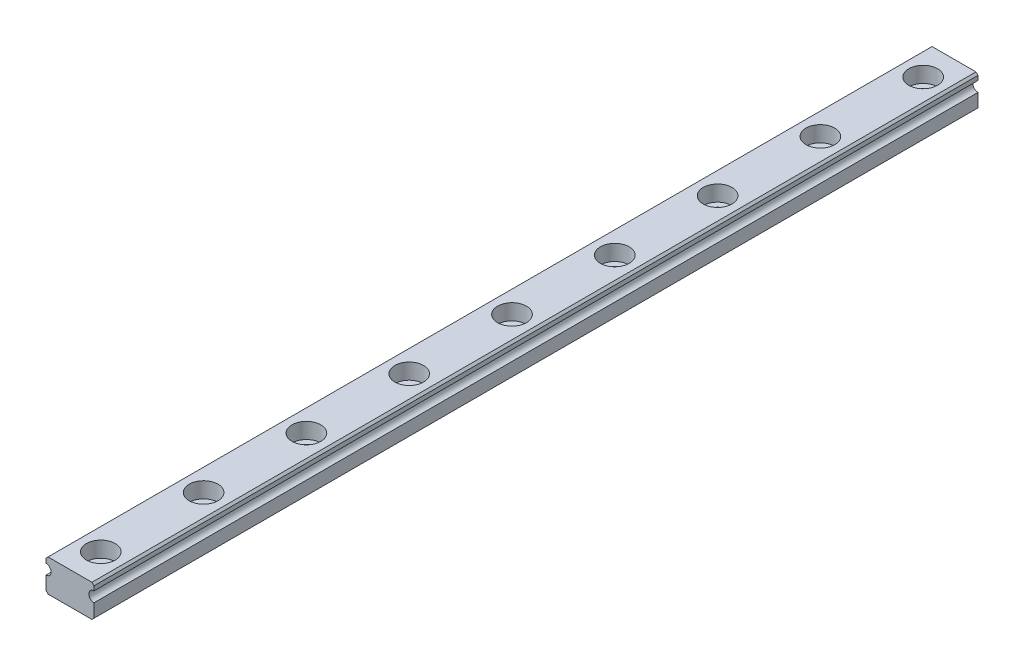
SolidWorks part; units mm, degrees
material "Plain Carbon Steel"
ref_plane "Front Plane" through (0, 0, 0) normal (0, 0, 1) x (1, 0, 0)
ref_plane "Top Plane" through (0, 0, 0) normal (0, 1, 0) x (1, 0, 0)
ref_plane "Right Plane" through (0, 0, 0) normal (1, 0, 0) x (0, 0, -1)
ref_plane "Plane1" through (0, 0, 0) normal (0, 0, 1) x (1, 0, 0)
sketch "Sketch1" plane through (0, 0, 0) normal (0, 0, 1) x (1, 0, 0)
  line L0 (-3.5, 4.403) -> (-3.5, 3.76)
  line L1 (-3.5, 2.26) -> (-3.5, 0.3)
  line L2 (-3.5, 0.3) -> (-3.2, 0)
  line L3 (-3.2, 0) -> (3.2, 0)
  line L4 (3.2, 0) -> (3.5, 0.3)
  line L5 (3.5, 0.3) -> (3.5, 2.26)
  line L6 (3.5, 3.76) -> (3.5, 4.403)
  line L7 (3.5, 4.403) -> (3.203, 4.7)
  line L8 (3.203, 4.7) -> (-3.203, 4.7)
  line L9 (-3.203, 4.7) -> (-3.5, 4.403)
  arc A0 (-3.5, 3.76) -> (-3.5, 2.26) centre (-3.5, 3.01) cw
  arc A1 (3.5, 2.26) -> (3.5, 3.76) centre (3.5, 3.01) cw
extrude "Boss-Extrude1" add sketch "Sketch1" along normal blind 129
ref_plane "Plane2" through (0, 0, 0) normal (1, 0, 0) x (0, 0, -1)
sketch "Sketch2" plane through (0, 0, 0) normal (1, 0, 0) x (0, 0, -1)
  line L0 (-4.5, 4.7) -> (-2.4, 4.7)
  line L1 (-2.4, 4.7) -> (-2.4, 2.4)
  line L2 (-2.4, 2.4) -> (-3.3, 2.4)
  line L3 (-3.3, 2.4) -> (-3.3, 0)
  line L4 (-3.3, 0) -> (-4.5, 0)
  line L5 (-4.5, 0) -> (-4.5, 4.7)
  line L6 (-4.5, 0) -> (-4.5, 4.7) construction
revolve "Cut-Revolve1" cut sketch "Sketch2" angle 360 about L6
ref_plane "Plane3" through (0, 0, 0) normal (1, 0, 0) x (0, 0, -1)
sketch "Sketch3" plane through (0, 0, 0) normal (1, 0, 0) x (0, 0, -1)
  line L0 (-124.5, 4.7) -> (-122.4, 4.7)
  line L1 (-122.4, 4.7) -> (-122.4, 2.4)
  line L2 (-122.4, 2.4) -> (-123.3, 2.4)
  line L3 (-123.3, 2.4) -> (-123.3, 0)
  line L4 (-123.3, 0) -> (-124.5, 0)
  line L5 (-124.5, 0) -> (-124.5, 4.7)
  line L6 (-124.5, 0) -> (-124.5, 4.7) construction
revolve "Cut-Revolve2" cut sketch "Sketch3" angle 360 about L6
ref_plane "Plane4" through (0, 0, 0) normal (1, 0, 0) x (0, 0, -1)
sketch "Sketch4" plane through (0, 0, 0) normal (1, 0, 0) x (0, 0, -1)
  line L0 (-109.5, 4.7) -> (-107.4, 4.7)
  line L1 (-107.4, 4.7) -> (-107.4, 2.4)
  line L2 (-107.4, 2.4) -> (-108.3, 2.4)
  line L3 (-108.3, 2.4) -> (-108.3, 0)
  line L4 (-108.3, 0) -> (-109.5, 0)
  line L5 (-109.5, 0) -> (-109.5, 4.7)
  line L6 (-109.5, 0) -> (-109.5, 4.7) construction
revolve "Cut-Revolve3" cut sketch "Sketch4" angle 360 about L6
ref_plane "Plane5" through (0, 0, 0) normal (1, 0, 0) x (0, 0, -1)
sketch "Sketch5" plane through (0, 0, 0) normal (1, 0, 0) x (0, 0, -1)
  line L0 (-94.5, 4.7) -> (-92.4, 4.7)
  line L1 (-92.4, 4.7) -> (-92.4, 2.4)
  line L2 (-92.4, 2.4) -> (-93.3, 2.4)
  line L3 (-93.3, 2.4) -> (-93.3, 0)
  line L4 (-93.3, 0) -> (-94.5, 0)
  line L5 (-94.5, 0) -> (-94.5, 4.7)
  line L6 (-94.5, 0) -> (-94.5, 4.7) construction
revolve "Cut-Revolve4" cut sketch "Sketch5" angle 360 about L6
ref_plane "Plane6" through (0, 0, 0) normal (1, 0, 0) x (0, 0, -1)
sketch "Sketch6" plane through (0, 0, 0) normal (1, 0, 0) x (0, 0, -1)
  line L0 (-79.5, 4.7) -> (-77.4, 4.7)
  line L1 (-77.4, 4.7) -> (-77.4, 2.4)
  line L2 (-77.4, 2.4) -> (-78.3, 2.4)
  line L3 (-78.3, 2.4) -> (-78.3, 0)
  line L4 (-78.3, 0) -> (-79.5, 0)
  line L5 (-79.5, 0) -> (-79.5, 4.7)
  line L6 (-79.5, 0) -> (-79.5, 4.7) construction
revolve "Cut-Revolve5" cut sketch "Sketch6" angle 360 about L6
ref_plane "Plane7" through (0, 0, 0) normal (1, 0, 0) x (0, 0, -1)
sketch "Sketch7" plane through (0, 0, 0) normal (1, 0, 0) x (0, 0, -1)
  line L0 (-64.5, 4.7) -> (-62.4, 4.7)
  line L1 (-62.4, 4.7) -> (-62.4, 2.4)
  line L2 (-62.4, 2.4) -> (-63.3, 2.4)
  line L3 (-63.3, 2.4) -> (-63.3, 0)
  line L4 (-63.3, 0) -> (-64.5, 0)
  line L5 (-64.5, 0) -> (-64.5, 4.7)
  line L6 (-64.5, 0) -> (-64.5, 4.7) construction
revolve "Cut-Revolve6" cut sketch "Sketch7" angle 360 about L6
ref_plane "Plane8" through (0, 0, 0) normal (1, 0, 0) x (0, 0, -1)
sketch "Sketch8" plane through (0, 0, 0) normal (1, 0, 0) x (0, 0, -1)
  line L0 (-49.5, 4.7) -> (-47.4, 4.7)
  line L1 (-47.4, 4.7) -> (-47.4, 2.4)
  line L2 (-47.4, 2.4) -> (-48.3, 2.4)
  line L3 (-48.3, 2.4) -> (-48.3, 0)
  line L4 (-48.3, 0) -> (-49.5, 0)
  line L5 (-49.5, 0) -> (-49.5, 4.7)
  line L6 (-49.5, 0) -> (-49.5, 4.7) construction
revolve "Cut-Revolve7" cut sketch "Sketch8" angle 360 about L6
ref_plane "Plane9" through (0, 0, 0) normal (1, 0, 0) x (0, 0, -1)
sketch "Sketch9" plane through (0, 0, 0) normal (1, 0, 0) x (0, 0, -1)
  line L0 (-34.5, 4.7) -> (-32.4, 4.7)
  line L1 (-32.4, 4.7) -> (-32.4, 2.4)
  line L2 (-32.4, 2.4) -> (-33.3, 2.4)
  line L3 (-33.3, 2.4) -> (-33.3, 0)
  line L4 (-33.3, 0) -> (-34.5, 0)
  line L5 (-34.5, 0) -> (-34.5, 4.7)
  line L6 (-34.5, 0) -> (-34.5, 4.7) construction
revolve "Cut-Revolve8" cut sketch "Sketch9" angle 360 about L6
ref_plane "Plane10" through (0, 0, 0) normal (1, 0, 0) x (0, 0, -1)
sketch "Sketch10" plane through (0, 0, 0) normal (1, 0, 0) x (0, 0, -1)
  line L0 (-19.5, 4.7) -> (-17.4, 4.7)
  line L1 (-17.4, 4.7) -> (-17.4, 2.4)
  line L2 (-17.4, 2.4) -> (-18.3, 2.4)
  line L3 (-18.3, 2.4) -> (-18.3, 0)
  line L4 (-18.3, 0) -> (-19.5, 0)
  line L5 (-19.5, 0) -> (-19.5, 4.7)
  line L6 (-19.5, 0) -> (-19.5, 4.7) construction
revolve "Cut-Revolve9" cut sketch "Sketch10" angle 360 about L6
